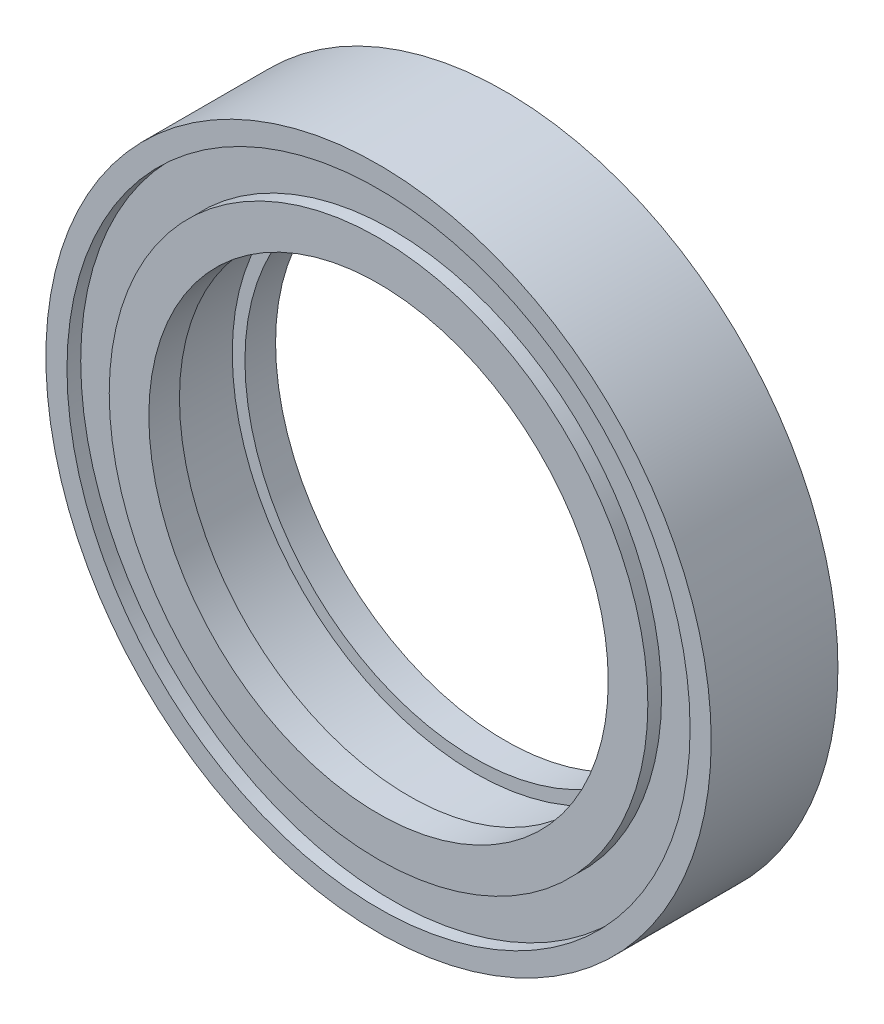
SolidWorks part; units mm, degrees
material "Custom Plastic"
ref_plane "Front Plane" through (0, 0, 0) normal (0, 0, 1) x (1, 0, 0)
ref_plane "Top Plane" through (0, 0, 0) normal (0, 1, 0) x (1, 0, 0)
ref_plane "Right Plane" through (0, 0, 0) normal (1, 0, 0) x (0, 0, -1)
sketch "Sketch1" plane through (0, 0, 0) normal (0, 1, 0) x (1, 0, 0)
  line L0 (0, -1000) -> (0, 49000) construction
  line L1 (-315, 60) -> (-295, 60)
  line L2 (-295, 60) -> (-295, 47)
  line L3 (-295, 47) -> (-255, 47)
  line L13 (-255, -47) -> (-295, -47)
  line L14 (-295, -47) -> (-295, -60)
  line L15 (-295, -60) -> (-315, -60)
  line L16 (-315, -60) -> (-315, 60)
  line L17 (-255, 47) -> (-255, 60)
  line L18 (-255, 60) -> (-217.5, 60)
  line L19 (-217.5, 60) -> (-217.5, 31)
  line L20 (-217.5, 31) -> (-229.5, 31)
  line L21 (-229.5, 31) -> (-229.5, -31)
  line L22 (-229.5, -31) -> (-217.5, -31)
  line L23 (-217.5, -31) -> (-217.5, -60)
  line L24 (-217.5, -60) -> (-255, -60)
  line L25 (-255, -60) -> (-255, -47)
  point P9 (-315, 0)
  point P14 (-275, -47)
  point P21 (-275, 47)
  dimension "D2" = 40
  dimension "D3" = 20
  dimension "D4" = 40
  dimension "D5" = 37.5
  dimension "D6" = 97.5
  dimension "D7" = 13
  dimension "D8" = 13
  dimension "D9" = 29
  dimension "D10" = 62
  dimension "D11" = 12
  dimension "D12" = 12
  dimension "D13" = 29
  dimension "D14" = 37.5
  dimension "D15" = 120
  dimension "D16" = 510
  dimension "D17" = 435
  dimension "D18" = 459
  dimension "D20" = 85.5
revolve "Revolve1" add sketch "Sketch1" angle 360 about L0
